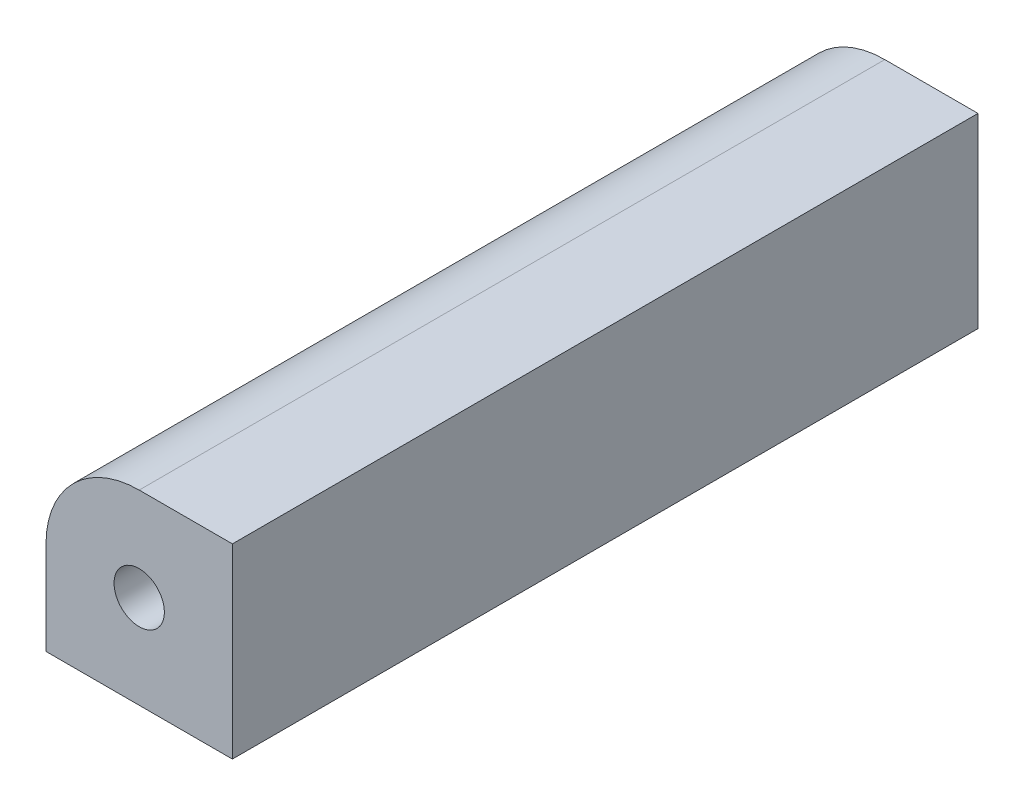
SolidWorks part; units mm, degrees
ref_plane "Front Plane" through (0, 0, 0) normal (0, 0, 1) x (1, 0, 0)
ref_plane "Top Plane" through (0, 0, 0) normal (0, 1, 0) x (1, 0, 0)
ref_plane "Right Plane" through (0, 0, 0) normal (1, 0, 0) x (0, 0, -1)
sketch "Sketch1" plane through (0, 0, 0) normal (0, 0, 1) x (1, 0, 0)
  line L0 (69, -42.5) -> (74, -42.5)
  line L2 (74, -42.5) -> (74, -52.5)
  line L3 (74, -52.5) -> (64, -52.5)
  line L5 (64, -47.5) -> (64, -52.5)
  arc A1 (69, -42.5) -> (64, -47.5) centre (69, -47.5) ccw
  circle A2 centre (69, -47.5) radius 1.35
  dimension "D3" = 2.7
  dimension "D1" = 10
  dimension "D2" = 10
extrude "Boss-Extrude1" add sketch "Sketch1" along normal blind 40
